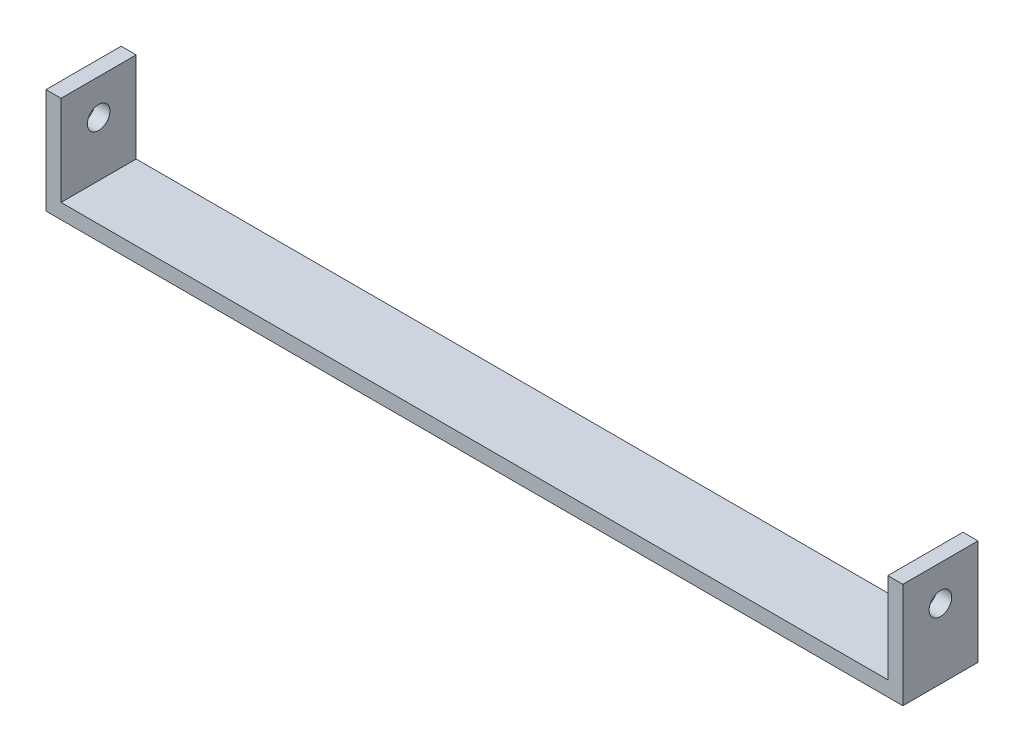
SolidWorks part; units mm, degrees
ref_plane "Plan de face" through (0, 0, 0) normal (0, 0, 1) x (1, 0, 0)
ref_plane "Plan de dessus" through (0, 0, 0) normal (0, 1, 0) x (1, 0, 0)
ref_plane "Plan de droite" through (0, 0, 0) normal (1, 0, 0) x (0, 0, -1)
sketch "Esquisse1" plane through (0, 0, 0) normal (0, 0, 1) x (1, 0, 0)
  line L0 (57, 0) -> (-57, 0)
  line L1 (-57, 0) -> (-57, 14)
  line L2 (-57, 14) -> (-55, 14)
  line L3 (-55, 14) -> (-55, 2)
  line L4 (-55, 2) -> (55, 2)
  line L5 (0, -4.5779) -> (0, 6.9307) construction
  line L6 (55, 14) -> (55, 2)
  line L7 (57, 14) -> (55, 14)
  line L8 (57, 0) -> (57, 14)
  point P9 (0, -4.5779)
  point P10 (0, 0)
  point P11 (0, 0)
  point P13 (0, 2)
  point P16 (0, 0)
  dimension "D1" = 2
  dimension "D2" = 2
  dimension "D3" = 114
  dimension "D4" = 14
extrude "Boss.-Extru.1" add sketch "Esquisse1" along normal blind 10
sketch "Esquisse2" plane through (-57, 0, 0) normal (-1, 0, 0) x (0, 0, 1)
  circle A0 centre (5, 9.2849) radius 1.5
  dimension "D1" = 3
extrude "Enlèv. mat.-Extru.1" cut sketch "Esquisse2" against normal through all both and the other way through all
